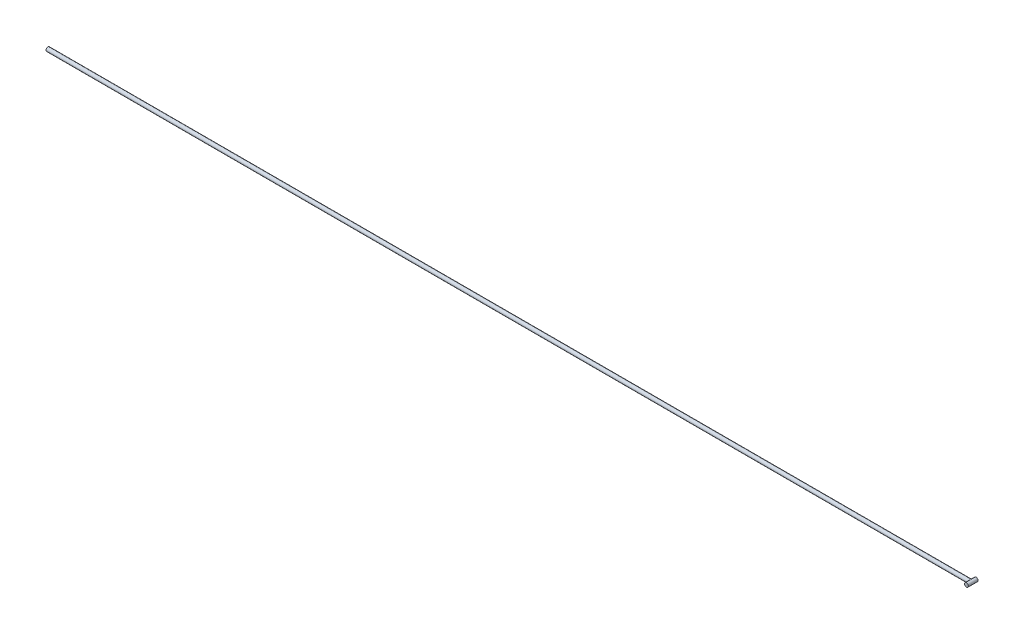
SolidWorks part; units mm, degrees
ref_plane "Plan de face" through (0, 0, 0) normal (0, 0, 1) x (1, 0, 0)
ref_plane "Plan de dessus" through (0, 0, 0) normal (0, 1, 0) x (1, 0, 0)
ref_plane "Plan de droite" through (0, 0, 0) normal (1, 0, 0) x (0, 0, -1)
sketch "Esquisse1" plane through (0, 0, 0) normal (0, 0, 1) x (1, 0, 0)
  line L0 (-239, 0) -> (239, 0)
  dimension "D1" = 478
sweep "Balayage1" add path "Esquisse1" circular profile diameter 2 parameters "D3"=2
sketch "Esquisse16" plane through (239, 0, 0) normal (1, 0, 0) x (0, 0, -1)
  line L0 (-2.5, 0) -> (2.5, 0)
  dimension "D1" = 5
sweep "Balayage2" add path "Esquisse16" circular profile diameter 2 parameters "D3"=2
